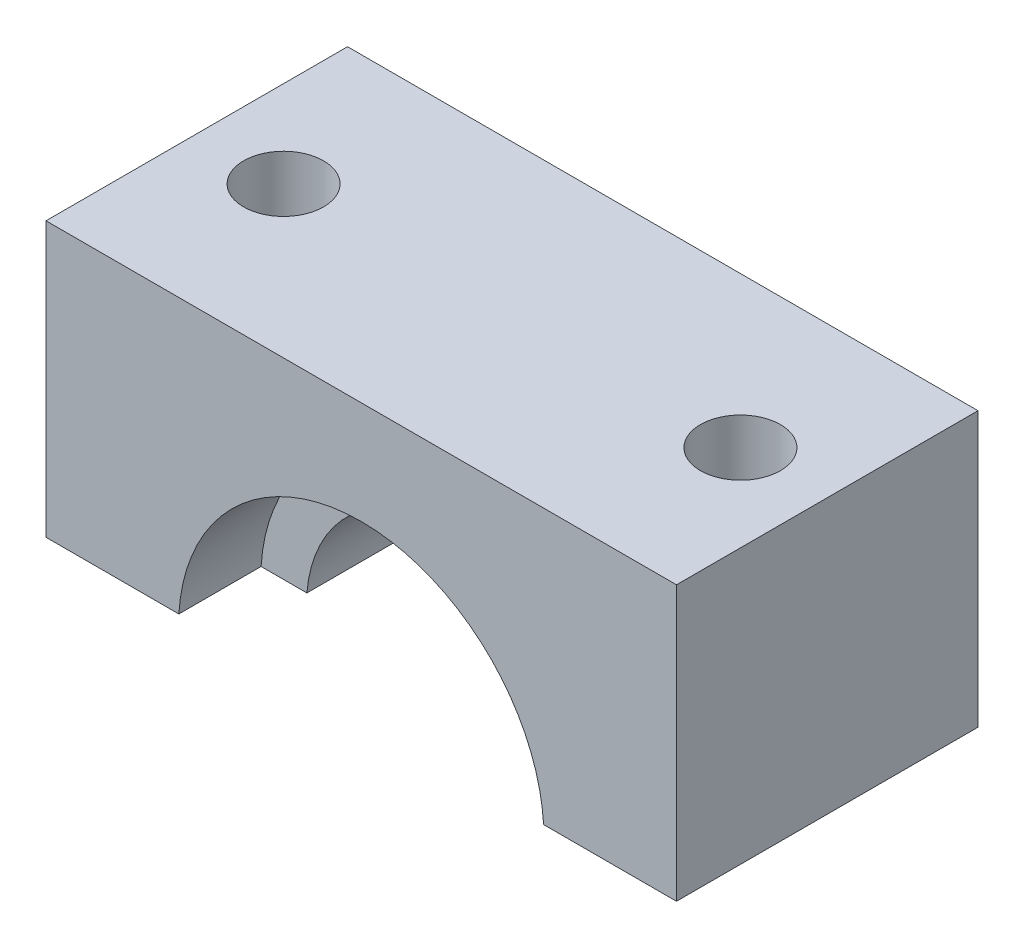
SolidWorks part; units mm, degrees
ref_plane "Piano frontale" through (0, 0, 0) normal (0, 0, 1) x (1, 0, 0)
ref_plane "Piano superiore" through (0, 0, 0) normal (0, 1, 0) x (1, 0, 0)
ref_plane "Piano destro" through (0, 0, 0) normal (1, 0, 0) x (0, 0, -1)
sketch "Schizzo1" plane through (0, 0, 0) normal (0, 0, 1) x (1, 0, 0)
  line L0 (0, 6.5) -> (0, -6.5) construction
  line L1 (14, -6.5) -> (-14, -6.5) construction
  line L2 (14, -6.5) -> (14, 6.5) construction
  line L3 (14, 6.5) -> (-14, 6.5) construction
  line L4 (-14, -6.5) -> (-14, 6.5) construction
  line L5 (14, -6.5) -> (-14, 6.5) construction
  line L6 (14, 6.5) -> (-14, -6.5) construction
  line L7 (-13.8, 6) -> (13.8, 6)
  line L8 (-13.8, 6) -> (-13.8, -6)
  line L9 (13.8, 6) -> (13.8, -6)
  line L10 (-13.8, -6) -> (-5.9791, -6)
  line L11 (5.9791, -6) -> (13.8, -6)
  arc A0 (5.9791, -6) -> (-5.9791, -6) centre (0, -6.5) ccw
  point P0 (0, 0)
  dimension "D6" = 6
  dimension "D1" = 13
  dimension "D2" = 28
  dimension "D3" = 0.2
  dimension "D4" = 0.2
  dimension "D5" = 0.5
  dimension "D7" = 0.5
extrude "Estrusione-Estrusione1" add sketch "Schizzo1" along normal mid plane 6
sketch "Schizzo2" plane through (0, 0, 0) normal (0, 0, 1) x (1, 0, 0)
  line L0 (13.8, 6) -> (-13.8, 6) construction
  line L1 (-13.8, 6) -> (-13.8, -6) construction
  line L2 (13.8, -6) -> (13.8, 6) construction
  line L3 (13.8, 6) -> (-13.8, 6)
  line L4 (-13.8, 6) -> (-13.8, -6)
  line L5 (13.8, -6) -> (13.8, 6)
  line L6 (-13.8, -6) -> (-7.9844, -6)
  line L7 (13.8, -6) -> (7.9844, -6)
  arc A0 (5.9791, -6) -> (-5.9791, -6) centre (0, -6.5) ccw construction
  arc A1 (5.9791, -6) -> (-5.9791, -6) centre (0, -6.5) ccw construction
  arc A2 (-7.9844, -6) -> (7.9844, -6) centre (0, -6.5) cw
  dimension "D1" = 8
extrude "Estrusione-Estrusione2" add sketch "Schizzo2" along normal mid plane 13.2
sketch "Schizzo3" plane through (0, -6, 0) normal (0, -1, 0) x (1, 0, 0)
  line L0 (-10, 0) -> (10, 0) construction
  circle A0 centre (-10, 0) radius 1.75
  circle A1 centre (10, 0) radius 1.75
  point P4 (0, 0)
  dimension "D2" = 3.5
  dimension "D1" = 20
extrude "Taglio-Estrusione1" cut sketch "Schizzo3" against normal through all
